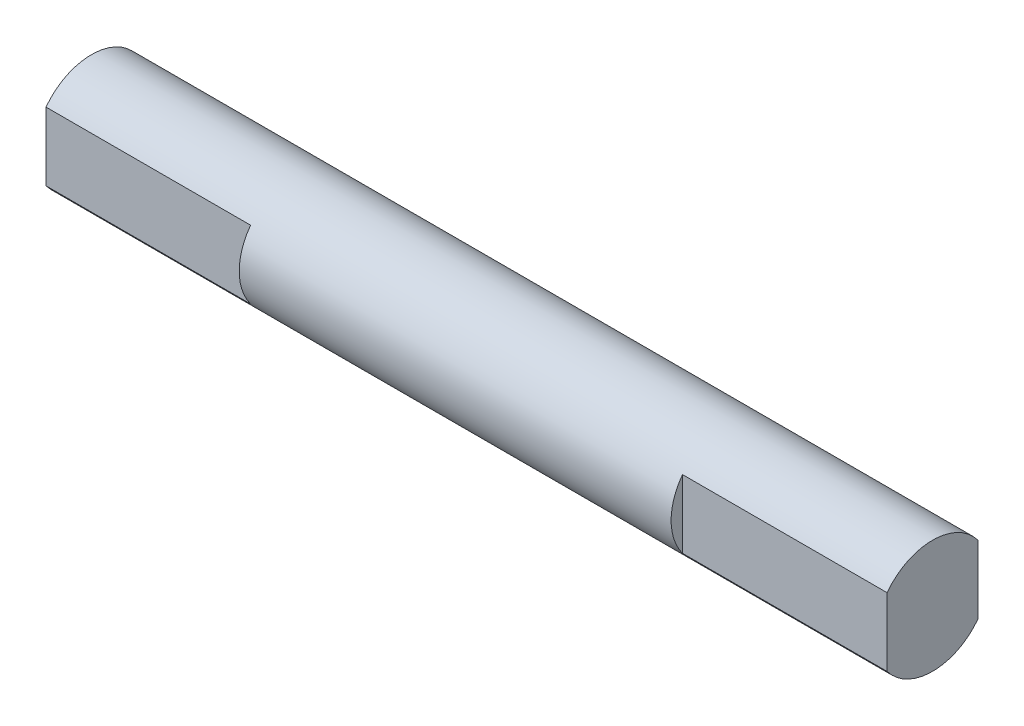
SolidWorks part; units mm, degrees
ref_plane "Front Plane" through (0, 0, 0) normal (0, 0, 1) x (1, 0, 0)
ref_plane "Top Plane" through (0, 0, 0) normal (0, 1, 0) x (1, 0, 0)
ref_plane "Right Plane" through (0, 0, 0) normal (1, 0, 0) x (0, 0, -1)
sketch "Sketch1" plane through (0, 0, 0) normal (1, 0, 0) x (0, 0, -1)
  circle A0 centre (0, 0) radius 2.5
  dimension "D1" = 5
extrude "Boss-Extrude1" add sketch "Sketch1" along normal mid plane 19
sketch "Sketch2" plane through (9.5, 0, 0) normal (1, 0, 0) x (0, 0, -1)
  line L0 (-2, 1.5) -> (-2, -1.5)
  line L1 (2, 1.5) -> (2, -1.5)
  arc A0 (2, 1.5) -> (-2, 1.5) centre (0, 0) ccw
  circle A1 centre (0, 0) radius 2.5
  arc A2 (-2, -1.5) -> (2, -1.5) centre (0, 0) ccw
  dimension "D2" = 2
  dimension "D3" = 2
  dimension "D1" = 0
extrude "Boss-Extrude2" add sketch "Sketch2" along normal blind 9
mirror "Mirror1" about plane through (0, 0, 0) normal (1, 0, 0) of "Boss-Extrude2"
